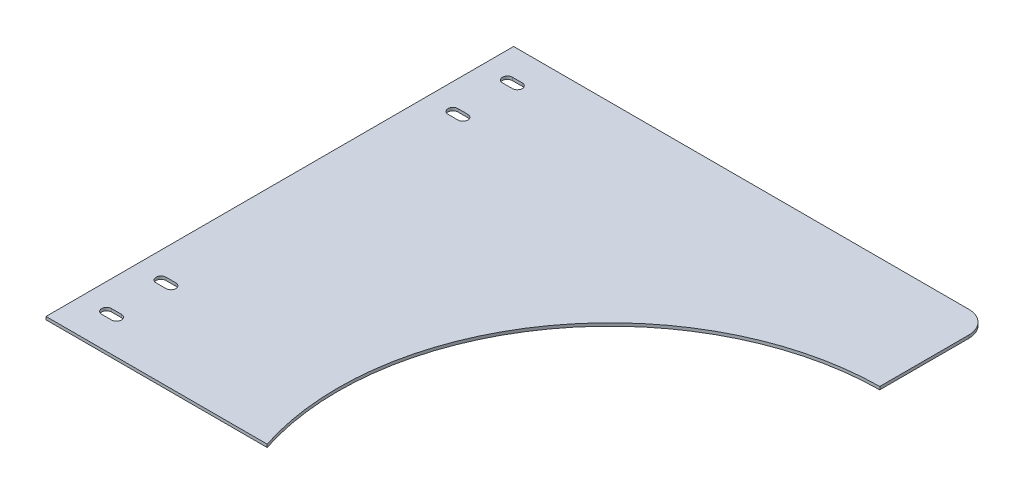
SolidWorks part; units mm, degrees
ref_plane "정면" through (0, 0, 0) normal (0, 0, 1) x (1, 0, 0)
ref_plane "윗면" through (0, 0, 0) normal (0, 1, 0) x (1, 0, 0)
ref_plane "우측면" through (0, 0, 0) normal (1, 0, 0) x (0, 0, -1)
sketch "스케치1" plane through (0, 0, 0) normal (0, 1, 0) x (1, 0, 0)
  line L0 (96.5, 85) -> (96.5, 48.9955)
  line L1 (-97.5, 95) -> (87.5, 95) construction
  line L2 (-97.5, 95) -> (-97.5, -95) construction
  line L3 (-97.5, -95) -> (97.5, -95) construction
  line L4 (97.5, 85) -> (97.5, -95) construction
  line L5 (-97.5, 95) -> (97.5, -95) construction
  line L6 (-97.5, -95) -> (97.5, 95) construction
  line L7 (-96.5, 94) -> (87.5, 94)
  line L8 (-96.5, 94) -> (-96.5, -95)
  line L9 (97.5, 0) -> (-97.5, 0) construction
  line L10 (-96.5, -95) -> (-7.1136, -95)
  line L11 (-97.5, 85) -> (-79, 85) construction
  line L12 (-97.5, 85) -> (-97.5, 55) construction
  line L13 (-97.5, 55) -> (-79, 55) construction
  line L14 (-79, 85) -> (-79, 55) construction
  line L15 (-84, 85) -> (-84, 55) construction
  line L16 (96.5, 85) -> (96.5, -95) construction
  line L17 (-79, 70) -> (-97.5, 70) construction
  line L18 (-86, 83) -> (-82, 83)
  line L19 (-86, 79) -> (-82, 79)
  line L20 (-86, 61) -> (-82, 61)
  line L21 (-86, 57) -> (-82, 57)
  line L22 (-79, -70) -> (-97.5, -70) construction
  line L23 (-84, -85) -> (-84, -55) construction
  line L24 (-79, -85) -> (-79, -55) construction
  line L25 (-97.5, -55) -> (-79, -55) construction
  line L26 (-97.5, -85) -> (-97.5, -55) construction
  line L27 (-97.5, -85) -> (-79, -85) construction
  line L28 (-86, -57) -> (-82, -57)
  line L29 (-86, -61) -> (-82, -61)
  line L30 (-86, -79) -> (-82, -79)
  line L31 (-86, -83) -> (-82, -83)
  arc A0 (97.5, 85) -> (87.5, 95) centre (87.5, 85) ccw construction
  circle A1 centre (97.5, -61) radius 110
  arc A2 (96.5, 85) -> (87.5, 94) centre (87.5, 85) ccw
  circle A3 centre (-84, 81) radius 2
  circle A5 centre (-82, 81) radius 2
  circle A6 centre (-86, 81) radius 2
  circle A7 centre (-86, 59) radius 2
  circle A8 centre (-82, 59) radius 2
  circle A9 centre (-84, 59) radius 2
  circle A10 centre (-84, -59) radius 2
  circle A11 centre (-82, -59) radius 2
  circle A12 centre (-86, -59) radius 2
  circle A13 centre (-86, -81) radius 2
  circle A14 centre (-82, -81) radius 2
  circle A15 centre (-84, -81) radius 2
  point P0 (0, 0)
  point P9 (97.5, 49)
  point P21 (0, 0)
  dimension "D3" = 10
  dimension "D5" = 220
  dimension "D12" = 4
  dimension "D1" = 190
  dimension "D2" = 195
  dimension "D4" = 36
  dimension "D7" = 10
  dimension "D8" = 30
  dimension "D9" = 18.5
  dimension "D10" = 5
  dimension "D11" = 22
  dimension "D6" = 1
extrude "보스-돌출1" add sketch "스케치1" along normal blind 1.2 contours L0 A2 L7 L8 L10 A1 A12 L28 A11 L29 A6 L18 A5 L19 L20 A8 L21 A7 L30 A14 L31 A13
